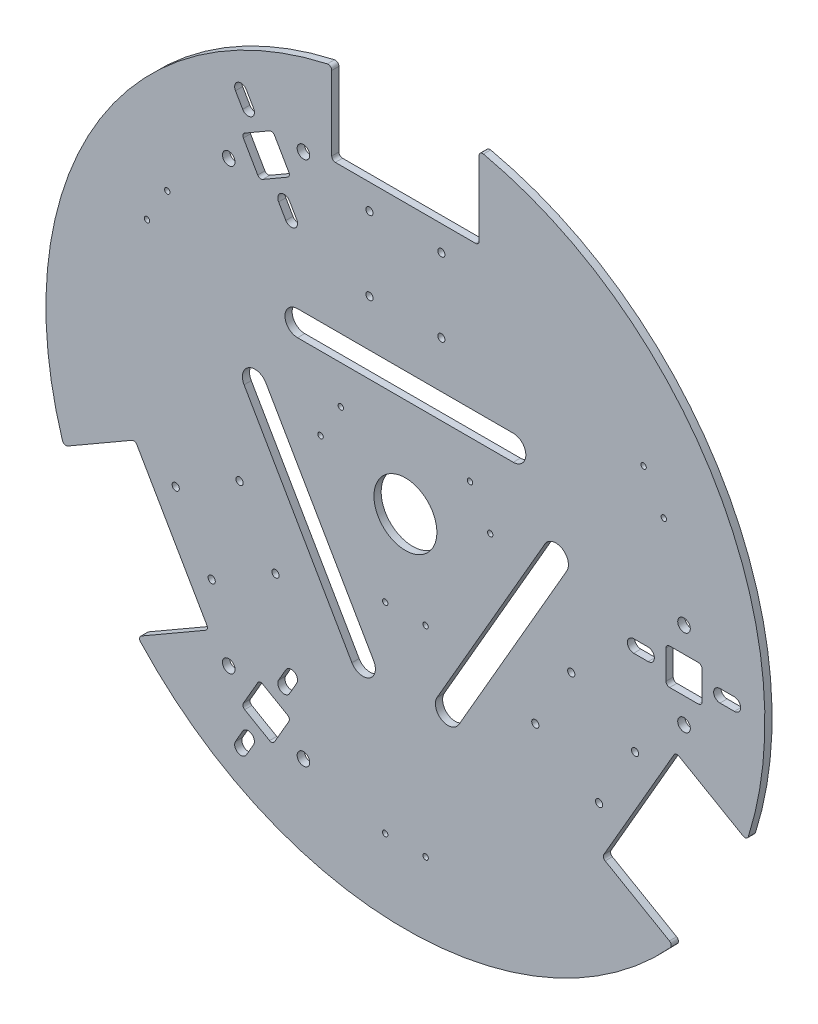
SolidWorks part; units mm, degrees
material "1060 Alloy"
ref_plane "Front Plane" through (0, 0, 0) normal (0, 0, 1) x (1, 0, 0)
ref_plane "Top Plane" through (0, 0, 0) normal (0, 1, 0) x (1, 0, 0)
ref_plane "Right Plane" through (0, 0, 0) normal (1, 0, 0) x (0, 0, -1)
sketch "Sketch1" plane through (0, 0, 0) normal (0, 0, 1) x (1, 0, 0)
  line L0 (0, 0) -> (-173.2051, 100) construction
  line L1 (0, 0) -> (173.2051, 100) construction
  line L2 (0, 0) -> (0, -200) construction
  line L3 (0, 0) -> (0, 200) construction
  circle A0 centre (0, 0) radius 200
  dimension "D1" = 400
  dimension "D2" = 120
  dimension "D3" = 120
extrude "Boss-Extrude2" add sketch "Sketch1" along normal blind 4
sketch "Sketch3" plane through (0, 0, 0) normal (0, 0, 1) x (1, 0, 0)
  line L0 (0, 0) -> (0, 200) construction
  line L3 (-41, 195.7524) -> (-41, 150)
  line L4 (-41, 150) -> (41, 150)
  line L5 (41, 195.7524) -> (41, 150)
  circle A0 centre (0, 0) radius 200 construction
  arc A1 (41, 195.7524) -> (-41, 195.7524) centre (0, 0) ccw
  dimension "D1" = 82
  dimension "D2" = 50
extrude "Cut-Extrude3" cut sketch "Sketch3" along normal up to surface (4 mm away) up to face at (200, 0, 4)
sketch "Sketch4" plane through (0, 0, 0) normal (0, 0, 1) x (1, 0, 0)
  circle A0 centre (0, 0) radius 17.5
  dimension "D1" = 35
extrude "Cut-Extrude4" cut sketch "Sketch4" along normal up to surface (4 mm away) up to face at (0, 73.9381, 4)
sketch "Sketch5" plane through (0, 0, 0) normal (0, 0, 1) x (1, 0, 0)
  line L0 (0, 0) -> (0, 200) construction
  circle A0 centre (-20, 136) radius 2
  circle A1 centre (-20, 95) radius 2
  circle A2 centre (20, 136) radius 2
  circle A3 centre (20, 95) radius 2
  dimension "D5" = 4
  dimension "D6" = 4
  dimension "D7" = 4
  dimension "D8" = 4
  dimension "D1" = 95
  dimension "D2" = 40
  dimension "D3" = 40
  dimension "D4" = 41
extrude "Cut-Extrude5" cut sketch "Sketch5" along normal up to surface (4 mm away) up to face at (17.5, 0, 4)
sketch "Sketch6" plane through (0, 0, 0) normal (0, 0, 1) x (1, 0, 0)
  line L0 (0, 0) -> (-199.1858, 115) construction
  line L1 (-132.5061, 89.4928) -> (-143.7561, 70.0072) construction
  line L2 (0, 0) -> (0, 171.0511) construction
  line L3 (-35.9442, 33.7428) -> (-47.1942, 14.2572) construction
  circle A1 centre (-143.7561, 70.0072) radius 1.5
  circle A2 centre (-132.5061, 89.4928) radius 1.5
  circle A3 centre (-35.9442, 33.7428) radius 1.5
  circle A4 centre (-47.1942, 14.2572) radius 1.5
  dimension "D1" = 3
  dimension "D2" = 3
  dimension "D3" = 3
  dimension "D4" = 3
  dimension "D8" = 48
  dimension "D5" = 22.5
  dimension "D6" = 22.5
  dimension "D7" = 111.5
  dimension "D9" = 60
extrude "Cut-Extrude6" cut sketch "Sketch6" along normal up to surface (4 mm away) up to face at (-18, 95, 4)
pattern_circular "CirPattern2" count 3 over 360 about axis through (0, 0, 0) along (0, 0, 1) of "Cut-Extrude6"
pattern_circular "CirPattern3" count 3 over 360 about axis through (0, 0, 0) along (0, 0, 1) of "Cut-Extrude5"
sketch "Sketch8" plane through (0, 0, 0) normal (0, 0, 1) x (1, 0, 0)
  line L0 (0, 0) -> (0, 200) construction
  line L2 (-60, 62) -> (60, 62) construction
  line L3 (-60, 69) -> (60, 69)
  line L4 (-60, 55) -> (60, 55)
  arc A0 (-60, 69) -> (-60, 55) centre (-60, 62) ccw
  arc A1 (60, 55) -> (60, 69) centre (60, 62) ccw
  point P7 (0, 62)
  point P22 (0, 55)
  dimension "D1" = 7
  dimension "D2" = 120
  dimension "D3" = 55
extrude "Cut-Extrude7" cut sketch "Sketch8" along normal up to surface (4 mm away) up to face at (129.7795, -50.6795, 4)
pattern_circular "CirPattern4" count 3 over 360 about axis through (0, 0, 0) along (0, 0, 1) of "Cut-Extrude7"
sketch "Sketch9" plane through (0, 0, 4) normal (0, 0, 1) x (1, 0, 0)
  line L0 (0, 0) -> (0, 200) construction
  line L2 (0, 0) -> (-115, 199.1858) construction
  line L3 (-91.1603, 137.8942) -> (-81.1603, 120.5737)
  line L4 (-73.8397, 147.8942) -> (-63.8397, 130.5737)
  line L5 (-91.1603, 137.8942) -> (-73.8397, 147.8942)
  line L6 (-81.1603, 120.5737) -> (-63.8397, 130.5737)
  line L7 (-86.1603, 129.2339) -> (-68.8397, 139.2339) construction
  line L8 (-67.5, 116.9134) -> (-63.5, 109.9852) construction
  line L9 (-64.4689, 118.6634) -> (-60.4689, 111.7352)
  line L10 (-70.5311, 115.1634) -> (-66.5311, 108.2352)
  line L11 (-87.5, 151.5544) -> (-91.5, 158.4826) construction
  line L12 (-84.4689, 153.3044) -> (-88.4689, 160.2326)
  line L13 (-90.5311, 149.8044) -> (-94.5311, 156.7326)
  circle A2 centre (-56.7154, 146.2339) radius 3.5
  arc A3 (-64.4689, 118.6634) -> (-70.5311, 115.1634) centre (-67.5, 116.9134) ccw
  arc A4 (-66.5311, 108.2352) -> (-60.4689, 111.7352) centre (-63.5, 109.9852) ccw
  circle A5 centre (-98.2846, 122.2339) radius 3.5
  arc A6 (-84.4689, 153.3044) -> (-90.5311, 149.8044) centre (-87.5, 151.5544) cw
  arc A7 (-94.5311, 156.7326) -> (-88.4689, 160.2326) centre (-91.5, 158.4826) cw
  point P19 (-65.5, 113.4493)
  point P28 (-89.5, 155.0185)
  dimension "D3" = 7
  dimension "D1" = 30
  dimension "D2" = 20
  dimension "D4" = 20
  dimension "D5" = 145
  dimension "D6" = 14
  dimension "D7" = 10
  dimension "D8" = 7
  dimension "D9" = 10
  dimension "D10" = 8
extrude "Cut-Extrude8" cut sketch "Sketch9" against normal up to surface (4 mm away) up to face at (-53.6936, -31, 0)
pattern_circular "CirPattern5" count 3 over 360 about axis through (0, 0, 0) along (0, 0, 1) of "Cut-Extrude8"
pattern_circular "CirPattern6" count 3 over 360 about axis through (0, 0, 0) along (0, 0, 1) of "Cut-Extrude3"
fillet "Fillet1" radius 2 12 edges at (149.0265, -133.3832, 2) (109.4038, -110.507, 2) (190.0265, -62.3692, 2) (150.4038, -39.493, 2) (-109.4038, -110.507, 2) (-149.0265, -133.3832, 2) (-150.4038, -39.493, 2) (-190.0265, -62.3692, 2) (41, 150, 2) (41, 195.7524, 2) (-41, 150, 2) (-41, 195.7524, 2)
fillet "Fillet2" radius 2 12 edges at (-73.8397, 147.8942, 2) (-91.1603, 137.8942, 2) (-63.8397, 130.5737, 2) (-81.1603, 120.5737, 2) (-73.8397, -147.8942, 2) (-63.8397, -130.5737, 2) (-91.1603, -137.8942, 2) (-81.1603, -120.5737, 2) (165, 10, 2) (165, -10, 2) (145, -10, 2) (145, 10, 2)
